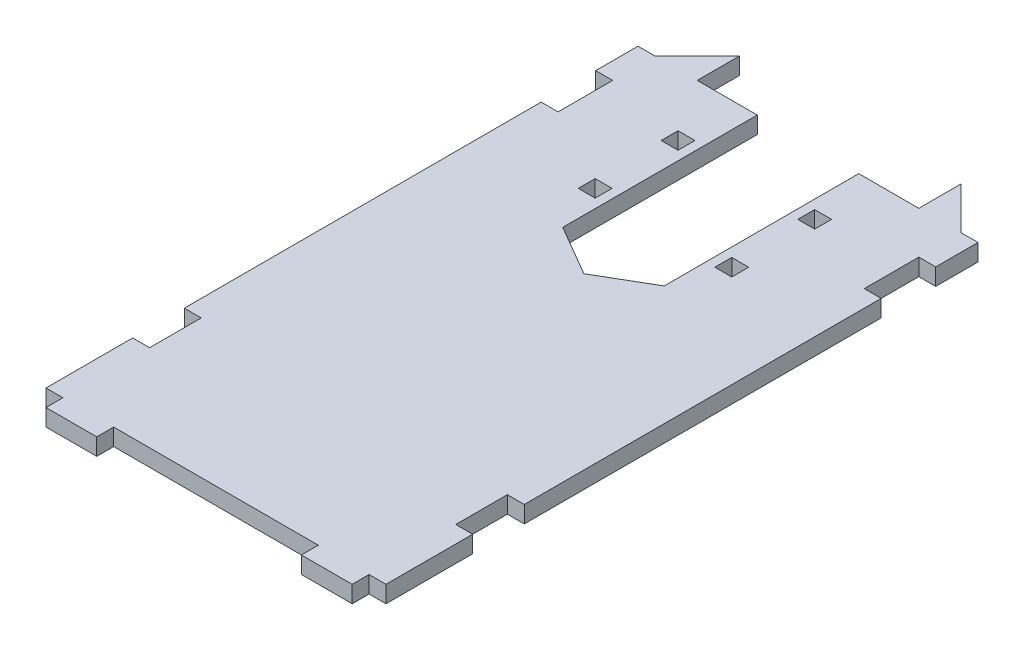
SolidWorks part; units mm, degrees
ref_plane "正面" through (0, 0, 0) normal (0, 0, 1) x (1, 0, 0)
ref_plane "平面" through (0, 0, 0) normal (0, 1, 0) x (1, 0, 0)
ref_plane "右側面" through (0, 0, 0) normal (1, 0, 0) x (0, 0, -1)
sketch "ｽｹｯﾁ1" plane through (0, 0, 0) normal (0, 1, 0) x (1, 0, 0)
  line L1 (0, 0) -> (40.2, 0)
  line L2 (0, 0) -> (0, 70)
  line L3 (0, 70) -> (40.2, 70)
  line L4 (40.2, 0) -> (40.2, 70)
  dimension "D1" = 40.2
  dimension "D2" = 70
extrude "ﾎﾞｽ - 押し出し1" add sketch "ｽｹｯﾁ1" along normal blind 2
sketch "ｽｹｯﾁ2" plane through (0, 2, 0) normal (0, 1, 0) x (1, 0, 0)
  line L0 (0, 70) -> (0, 0) construction
  line L1 (0, 10.25) -> (2, 10.25)
  line L2 (0, 10.25) -> (0, 16.35)
  line L3 (0, 16.35) -> (2, 16.35)
  line L4 (2, 10.25) -> (2, 16.35)
  line L5 (0, 0) -> (40.2, 0) construction
  line L6 (40.2, 0) -> (40.2, 70) construction
  line L7 (40.2, 10.25) -> (38.2, 10.25)
  line L8 (40.2, 10.25) -> (40.2, 16.35)
  line L9 (40.2, 16.35) -> (38.2, 16.35)
  line L10 (38.2, 10.25) -> (38.2, 16.35)
  line L11 (40.2, 70) -> (0, 70) construction
  line L12 (0, 65) -> (2, 65)
  line L13 (0, 65) -> (0, 58.55)
  line L14 (0, 58.55) -> (2, 58.55)
  line L15 (2, 65) -> (2, 58.55)
  line L17 (40.2, 65) -> (38.2, 65)
  line L18 (40.2, 65) -> (40.2, 58.55)
  line L19 (40.2, 58.55) -> (38.2, 58.55)
  line L20 (38.2, 65) -> (38.2, 58.55)
  dimension "D1" = 10.25
  dimension "D2" = 6.1
  dimension "D3" = 2
  dimension "D4" = 2
  dimension "D5" = 5
  dimension "D6" = 6.45
extrude "ｶｯﾄ - 押し出し1" cut sketch "ｽｹｯﾁ2" against normal through all
sketch "ｽｹｯﾁ3" plane through (0, 0, 0) normal (0, 0, 1) x (1, 0, 0)
  line L0 (0, 2) -> (40.2, 2) construction
  line L1 (2, 2) -> (8, 2)
  line L2 (2, 2) -> (2, 0)
  line L3 (2, 0) -> (8, 0)
  line L4 (8, 2) -> (8, 0)
  line L5 (0, 0) -> (40.2, 0) construction
  line L6 (2, 0) -> (2, 2) construction
  line L7 (38.2, 0) -> (38.2, 2) construction
  line L8 (38.2, 2) -> (32.2, 2)
  line L9 (38.2, 2) -> (38.2, 0)
  line L10 (38.2, 0) -> (32.2, 0)
  line L11 (32.2, 2) -> (32.2, 0)
  dimension "D1" = 0
  dimension "D2" = 6
  dimension "D3" = 0
  dimension "D4" = 6
extrude "ﾎﾞｽ - 押し出し2" add sketch "ｽｹｯﾁ3" along normal blind 2
sketch "ｽｹｯﾁ4" plane through (0, 0, -70) normal (0, 0, -1) x (-1, 0, 0)
  line L0 (-40.2, 2) -> (0, 2) construction
  line L1 (-38.2, 2) -> (-33.2, 2)
  line L2 (-38.2, 2) -> (-38.2, 0)
  line L3 (-38.2, 0) -> (-33.2, 0)
  line L4 (-33.2, 2) -> (-33.2, 0)
  line L5 (-40.2, 0) -> (0, 0) construction
  line L6 (-38.2, 0) -> (-38.2, 2) construction
  line L7 (-2, 2) -> (-7, 2)
  line L8 (-2, 2) -> (-2, 0)
  line L9 (-2, 0) -> (-7, 0)
  line L10 (-7, 2) -> (-7, 0)
  line L11 (-2, 0) -> (-2, 2) construction
  dimension "D1" = 0
  dimension "D2" = 5
  dimension "D3" = 0
  dimension "D4" = 5
extrude "ﾎﾞｽ - 押し出し3" add sketch "ｽｹｯﾁ4" along normal blind 5
sketch "ｽｹｯﾁ5" plane through (0, 2, 0) normal (0, 1, 0) x (1, 0, 0)
  line L0 (7, 75) -> (2, 70)
  line L1 (2, 70) -> (2, 75)
  line L2 (2, 75) -> (7, 75)
  line L3 (33.2, 75) -> (38.2, 70)
  line L4 (38.2, 70) -> (38.2, 75)
  line L5 (38.2, 75) -> (33.2, 75)
extrude "ｶｯﾄ - 押し出し2" cut sketch "ｽｹｯﾁ5" against normal through all
sketch "ｽｹｯﾁ6" plane through (0, 2, 0) normal (0, 1, 0) x (1, 0, 0)
  line L0 (20.1, 0) -> (20.1, 84.891) construction
  line L1 (8, 0) -> (32.2, 0) construction
sketch "ｽｹｯﾁ7" plane through (0, 2, 0) normal (0, 1, 0) x (1, 0, 0)
  line L0 (14.1, 70) -> (14.1, 47)
  line L1 (33.2, 70) -> (7, 70) construction
  line L2 (14.1, 47) -> (20.1, 43.5)
  line L3 (20.1, 0) -> (20.1, 84.891) construction
  line L4 (20.1, 43.5) -> (26.1, 47)
  line L5 (26.1, 47) -> (26.1, 70)
  line L6 (26.1, 70) -> (14.1, 70)
  dimension "D1" = 6
  dimension "D2" = 6
  dimension "D3" = 23
  dimension "D4" = 23
  dimension "D5" = 26.5
extrude "ｶｯﾄ - 押し出し3" cut sketch "ｽｹｯﾁ7" against normal blind 5
sketch "ｽｹｯﾁ8" plane through (0, 2, 0) normal (0, 1, 0) x (1, 0, 0)
  line L1 (11.025, 63.71) -> (13.025, 63.71)
  line L2 (11.025, 63.71) -> (11.025, 61.71)
  line L3 (11.025, 61.71) -> (13.025, 61.71)
  line L4 (13.025, 63.71) -> (13.025, 61.71)
  line L5 (14.1, 70) -> (7, 70) construction
  line L7 (11.025, 53.91) -> (13.025, 53.91)
  line L8 (11.025, 53.91) -> (11.025, 51.91)
  line L9 (11.025, 51.91) -> (13.025, 51.91)
  line L10 (13.025, 53.91) -> (13.025, 51.91)
  line L11 (27.175, 63.71) -> (29.175, 63.71)
  line L12 (27.175, 63.71) -> (27.175, 61.71)
  line L13 (27.175, 61.71) -> (29.175, 61.71)
  line L14 (29.175, 63.71) -> (29.175, 61.71)
  line L15 (33.2, 70) -> (26.1, 70) construction
  line L16 (20.1, 0) -> (20.1, 84.891) construction
  line L17 (27.175, 53.91) -> (29.175, 53.91)
  line L18 (27.175, 53.91) -> (27.175, 51.91)
  line L19 (27.175, 51.91) -> (29.175, 51.91)
  line L20 (29.175, 53.91) -> (29.175, 51.91)
  dimension "D1" = 2
  dimension "D2" = 2
  dimension "D3" = 7.075
  dimension "D4" = 6.29
  dimension "D5" = 2
  dimension "D6" = 2
  dimension "D7" = 7.8
  dimension "D8" = 2
  dimension "D9" = 2
  dimension "D10" = 7.075
  dimension "D11" = 6.29
  dimension "D12" = 7.075
  dimension "D13" = 7.075
extrude "ｶｯﾄ - 押し出し4" cut sketch "ｽｹｯﾁ8" against normal blind 5
